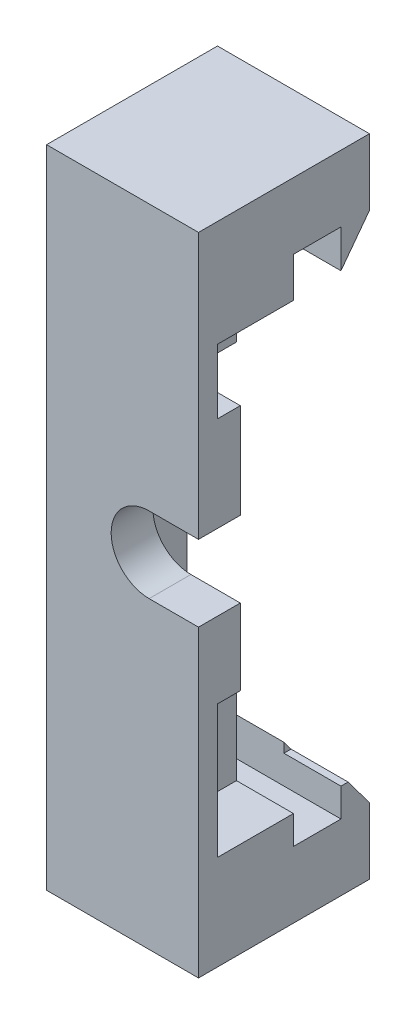
SolidWorks part; units mm, degrees
ref_plane "Front Plane" through (0, 0, 0) normal (0, 0, 1) x (1, 0, 0)
ref_plane "Top Plane" through (0, 0, 0) normal (0, 1, 0) x (1, 0, 0)
ref_plane "Right Plane" through (0, 0, 0) normal (1, 0, 0) x (0, 0, -1)
sketch "Sketch1" plane through (0, 0, 0) normal (0, 0, 1) x (1, 0, 0)
  line L1 (0, 0) -> (4, 0)
  line L2 (0, 0) -> (0, 17)
  line L3 (0, 17) -> (4, 17)
  line L4 (4, 0) -> (4, 17)
  dimension "D1" = 17
  dimension "D2" = 4
extrude "Boss-Extrude1" add sketch "Sketch1" along normal blind 6
sketch "Sketch2" plane through (0, 0, 6) normal (0, 0, 1) x (1, 0, 0)
  line L0 (4, 0) -> (4, 17) construction
  line L1 (4, 12.5) -> (1.2, 12.5)
  line L2 (4, 12.5) -> (4, 6)
  line L3 (4, 6) -> (1.2, 6)
  line L4 (1.2, 12.5) -> (1.2, 6)
  line L5 (4, 17) -> (0, 17) construction
  line L6 (0, 0) -> (4, 0) construction
  line L7 (0, 17) -> (0, 0) construction
  line L9 (4, 5.25) -> (2.5, 5.25)
  line L10 (4, 5.25) -> (4, 2.5)
  line L11 (4, 2.5) -> (2.5, 2.5)
  line L12 (2.5, 5.25) -> (2.5, 2.5)
  point P6 (2.6, 12.5)
  dimension "D1" = 4.5
  dimension "D2" = 6
  dimension "D3" = 1.2
  dimension "D4" = 1.5
  dimension "D5" = 2.5
  dimension "D6" = 0.75
extrude "Cut-Extrude1" cut sketch "Sketch2" against normal through all
sketch "Sketch3" plane through (0, 0, 0) normal (-1, 0, 0) x (0, 0, 1)
  line L0 (0, 15.25) -> (0.75, 14.25)
  line L1 (0, 17) -> (0, 0) construction
  line L2 (0.75, 14.25) -> (0.75, 15.25)
  line L3 (0.75, 15.25) -> (2, 15.25)
  line L4 (2, 15.25) -> (2, 1.75)
  line L5 (0, 15.25) -> (0, 1.75)
  line L6 (-999.8573, 8.5) -> (49000.1427, 8.5) construction
  line L7 (6, 17) -> (0, 17) construction
  line L8 (6, 17) -> (6, 0) construction
  line L9 (0.75, 1.75) -> (2, 1.75)
  line L10 (0.75, 2.75) -> (0.75, 1.75)
  line L11 (0, 1.75) -> (0.75, 2.75)
  point P17 (0, 8.5)
  point P18 (2, 8.5)
  dimension "D1" = 1.75
  dimension "D2" = 4
  dimension "D3" = 1.25
  dimension "D4" = 1.75
  dimension "D5" = 1
extrude "Cut-Extrude2" cut sketch "Sketch3" against normal through all
sketch "Sketch4" plane through (4, 0, 0) normal (1, 0, 0) x (0, 0, -1)
  line L0 (-2, 2.5) -> (-6, 2.5) construction
  line L1 (-6, 5.25) -> (-4, 5.25)
  line L2 (-6, 5.25) -> (-6, 2.5)
  line L3 (-6, 2.5) -> (-4, 2.5)
  line L4 (-4, 5.25) -> (-4, 2.5)
  dimension "D1" = 2
extrude "Boss-Extrude2" add sketch "Sketch4" against normal blind 2
sketch "Sketch6" plane through (0, 0, 2) normal (0, 0, -1) x (-1, 0, 0)
  line L1 (-4, 12.5) -> (-2.5, 12.5)
  line L2 (-4, 12.5) -> (-4, 14.2)
  line L3 (-4, 14.2) -> (-2.5, 14.2)
  line L4 (-2.5, 12.5) -> (-2.5, 14.2)
  line L5 (-2.5, 5.25) -> (-4, 5.25)
  line L6 (-2.5, 5.25) -> (-2.5, 6)
  line L7 (-2.5, 6) -> (-4, 6)
  line L8 (-4, 5.25) -> (-4, 6)
  dimension "D1" = 1.5
  dimension "D2" = 1.7
extrude "Cut-Extrude3" cut sketch "Sketch6" against normal blind 2
sketch "Sketch7" plane through (1.2, 0, 0) normal (1, 0, 0) x (0, 0, -1)
  line L0 (-2, 6) -> (-6, 6) construction
  line L1 (-6, 12.5) -> (-3.4, 12.5)
  line L2 (-6, 12.5) -> (-6, 6)
  line L3 (-6, 6) -> (-3.4, 6)
  line L4 (-3.4, 12.5) -> (-3.4, 6)
  line L5 (-2, 6) -> (-2, 12.5) construction
  dimension "D1" = 1.4
extrude "Boss-Extrude3" add sketch "Sketch7" along normal up to surface (2.8 mm away) up to face at (4, 14.74, 2.55)
sketch "Sketch8" plane through (0, 0, 3.4) normal (0, 0, -1) x (-1, 0, 0)
  line L0 (-4, 17) -> (0, 17) construction
  line L1 (-1.2, 6) -> (-1.2, 12.5) construction
  line L2 (-2.7, 10) -> (-4, 10)
  line L3 (-4, 12.5) -> (-4, 6) construction
  line L4 (-4, 10) -> (-4, 8)
  line L5 (-4, 8) -> (-2.7, 8)
  circle A0 centre (-2.7, 9) radius 1 construction
  arc A1 (-2.7, 10) -> (-2.7, 8) centre (-2.7, 9) cw
  dimension "D2" = 2
  dimension "D1" = 8
  dimension "D3" = 1.5
extrude "Cut-Extrude4" cut sketch "Sketch8" against normal blind 10
sketch "Sketch9" plane through (4, 0, 0) normal (1, 0, 0) x (0, 0, -1)
  line L0 (-6, 0) -> (0, 0) construction
  line L1 (-6, 17) -> (-4.5, 17)
  line L2 (-6, 17) -> (-6, 0)
  line L3 (-6, 0) -> (-4.5, 0)
  line L4 (-4.5, 17) -> (-4.5, 0)
  line L5 (-2, 6) -> (-2, 12.5) construction
  dimension "D1" = 2.5
extrude "Cut-Extrude5" cut sketch "Sketch9" against normal through all
